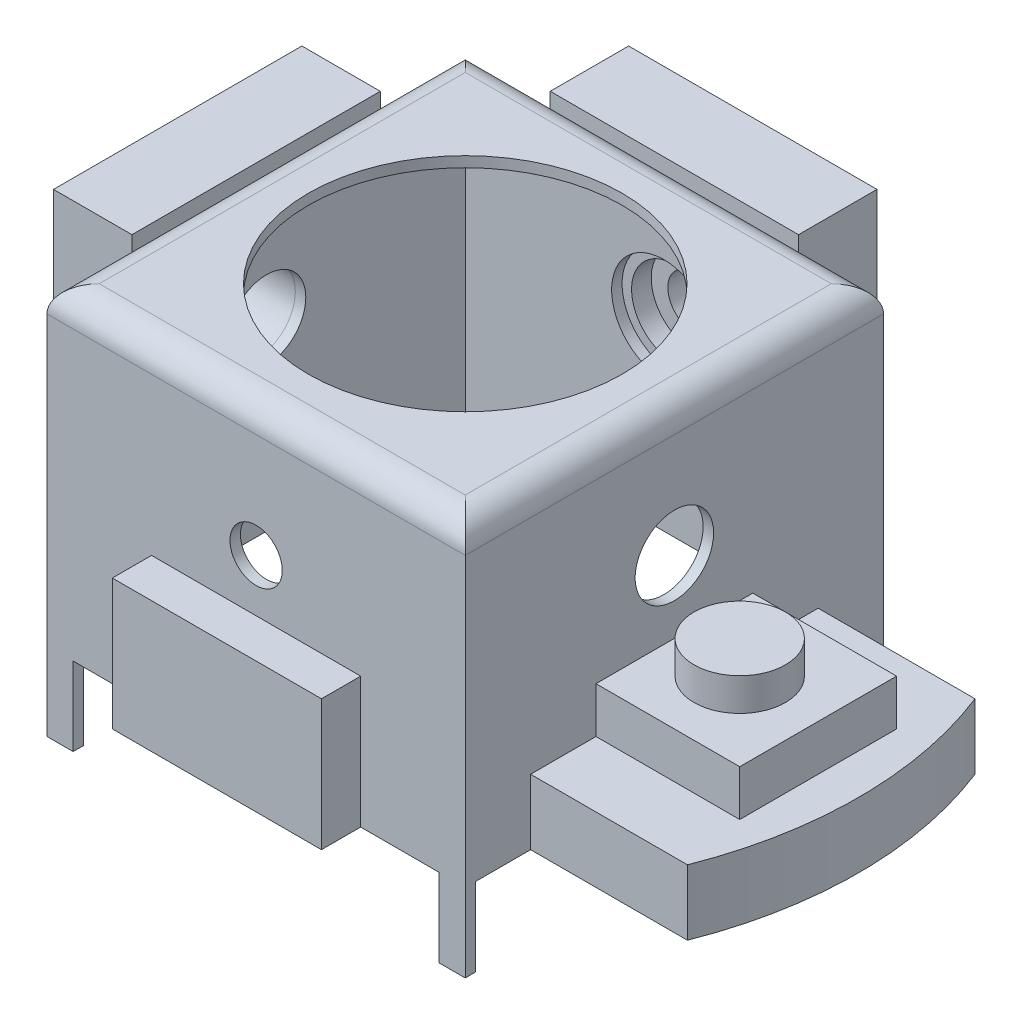
SolidWorks part; units mm, degrees
ref_plane "Front" through (0, 0, 0) normal (0, 0, 1) x (1, 0, 0)
ref_plane "Top" through (0, 0, 0) normal (0, 1, 0) x (1, 0, 0)
ref_plane "Right" through (0, 0, 0) normal (1, 0, 0) x (0, 0, -1)
sketch "Sketch1" plane through (0, 0, 0) normal (0, 1, 0) x (1, 0, 0)
  line L1 (-8, -8) -> (8, -8)
  line L2 (-8, -8) -> (-8, 8)
  line L3 (-8, 8) -> (8, 8)
  line L4 (8, -8) -> (8, 8)
  line L5 (-8, -8) -> (8, 8) construction
  line L6 (-8, 8) -> (8, -8) construction
  point P0 (0, 0)
  dimension "D1" = 16
extrude "Extrude1" add sketch "Sketch1" along normal blind 12
fillet "Fillet1" radius 1 4 edges at (0, 12, 8) (-8, 12, 0) (0, 12, -8) (8, 12, 0)
shell "Shell1" thickness 0.4
sketch "Sketch2" plane through (0, 12, 0) normal (0, 1, 0) x (1, 0, 0)
  circle A0 centre (0, 0) radius 6
  dimension "D1" = 12
extrude "Extrude2" cut sketch "Sketch2" against normal through all
sketch "Sketch4" plane through (0, 0, 0) normal (0, 1, 0) x (1, 0, 0)
  line L0 (8, -8) -> (-8, -8) construction
  line L1 (-4, -8) -> (4, -8)
  line L2 (-4, -8) -> (-4, -9.5)
  line L3 (-4, -9.5) -> (4, -9.5)
  line L4 (4, -8) -> (4, -9.5)
  line L5 (0, -6.6) -> (0, 6.6) construction
  point P6 (0, -9.5)
  dimension "D1" = 1.5
  dimension "D2" = 8
extrude "Extrude3" add sketch "Sketch4" along normal blind 5 separate body
sketch "Sketch5" plane through (0, 0, 0) normal (0, 1, 0) x (1, 0, 0)
  line L0 (-8, -8) -> (-8, 8) construction
  line L1 (-8, 4.75) -> (-11, 4.75)
  line L2 (-8, 4.75) -> (-8, -4.75)
  line L3 (-8, -4.75) -> (-11, -4.75)
  line L4 (-11, 4.75) -> (-11, -4.75)
  line L5 (-6.6, 0) -> (6.6, 0) construction
  point P6 (-11, 0)
  dimension "D1" = 9.5
  dimension "D2" = 3
extrude "Extrude4" add sketch "Sketch5" along normal blind 11 from offset 1 separate body
sketch "Sketch6" plane through (0, 0, 0) normal (0, 1, 0) x (1, 0, 0)
  line L0 (-8, 8) -> (8, 8) construction
  line L1 (-4.75, 8) -> (4.75, 8)
  line L2 (-4.75, 8) -> (-4.75, 11)
  line L3 (-4.75, 11) -> (4.75, 11)
  line L4 (4.75, 8) -> (4.75, 11)
  line L5 (0, -6.6) -> (0, 6.6) construction
  line L6 (-11, 4.75) -> (-11, -4.75) construction
  line L7 (-8, 4.75) -> (-11, 4.75) construction
  point P6 (0, 11)
extrude "Extrude5" add sketch "Sketch6" along normal blind 11 from offset 1 separate body
sketch "Sketch7" plane through (0, 0, 0) normal (0, 1, 0) x (1, 0, 0)
  line L0 (8, 5.5) -> (14, 5.5)
  line L1 (8, 8) -> (8, -8) construction
  line L2 (-1001.9415, 0) -> (48998.0585, 0) construction
  line L4 (-8.25, 0) -> (8.25, 0) construction
  line L5 (8, -5.5) -> (14, -5.5)
  line L6 (8, 5.5) -> (8, -5.5)
  arc A0 (14, 5.5) -> (14, -5.5) centre (0, 0) cw
  dimension "D1" = 6
  dimension "D2" = 11
extrude "Extrude6" add sketch "Sketch7" along normal blind 2.5 separate body
sketch "Sketch8" plane through (0, 2.5, 0) normal (0, 1, 0) x (1, 0, 0)
  line L0 (8, 5.5) -> (8, -5.5) construction
  line L1 (8, 3) -> (13.5, 3)
  line L2 (8, 3) -> (8, -3)
  line L3 (8, -3) -> (13.5, -3)
  line L4 (13.5, 3) -> (13.5, -3)
  line L5 (-8.25, 0) -> (8.25, 0) construction
  point P6 (13.5, 0)
  dimension "D1" = 6
  dimension "D2" = 5.5
extrude "Extrude7" add sketch "Sketch8" along normal blind 1.75 separate body
sketch "Sketch9" plane through (0, 4.25, 0) normal (0, 1, 0) x (1, 0, 0)
  line L0 (-8.25, 0) -> (8.25, 0) construction
  line L1 (13.5, -3) -> (13.5, 3) construction
  circle A0 centre (10.5, 0) radius 1.75
  dimension "D1" = 3.5
  dimension "D2" = 1.25
extrude "Extrude8" add sketch "Sketch9" along normal blind 1.25
sketch "Sketch10" plane through (0, 0, 0) normal (0, 0, 1) x (1, 0, 0)
  line L0 (0, -6.6) -> (0, 6.6) construction
  line L1 (11.275, 0) -> (-11.275, 0) construction
  circle A0 centre (0, 7) radius 1
  dimension "D1" = 2
  dimension "D2" = 7
extrude "Extrude9" cut sketch "Sketch10" against normal through all and the other way through all
sketch "Sketch11" plane through (0, 0, 0) normal (1, 0, 0) x (0, 0, -1)
  line L0 (0, 6.6) -> (0, -6.6) construction
  line L1 (11.275, 0) -> (-11.275, 0) construction
  circle A0 centre (0, 7) radius 1
  dimension "D1" = 2
  dimension "D2" = 7
extrude "Extrude10" cut sketch "Sketch11" against normal through all and the other way through all
sketch "Sketch12" plane through (0, 0, 0) normal (0, 1, 0) x (1, 0, 0)
  line L0 (-7.6, 7.6) -> (7.6, 7.6) construction
  line L1 (8, 8) -> (7, 8)
  line L2 (8, 8) -> (8, 7.6)
  line L3 (8, 7.6) -> (7, 7.6)
  line L4 (7, 8) -> (7, 7.6)
  line L5 (7.6, -7.6) -> (-7.6, -7.6) construction
  line L6 (-8, 8) -> (-7, 8)
  line L7 (-8, 8) -> (-8, 7.6)
  line L8 (-8, 7.6) -> (-7, 7.6)
  line L9 (-7, 8) -> (-7, 7.6)
  line L10 (8, -8) -> (7, -8)
  line L11 (8, -8) -> (8, -7.6)
  line L12 (8, -7.6) -> (7, -7.6)
  line L13 (7, -8) -> (7, -7.6)
  line L15 (-8, -8) -> (-7, -8)
  line L16 (-8, -8) -> (-8, -7.6)
  line L17 (-8, -7.6) -> (-7, -7.6)
  line L18 (-7, -8) -> (-7, -7.6)
  dimension "D1" = 1
extrude "Extrude11" add sketch "Sketch12" against normal blind 3
sketch "Sketch13" plane through (0, 0, -7.6) normal (0, 0, 1) x (1, 0, 0)
  circle A0 centre (0, 7) radius 1.5
  dimension "D1" = 3
extrude "Extrude12" cut sketch "Sketch13" against normal up to next (0.4 mm away)
sketch "Sketch14" plane through (-7.6, 0, 0) normal (1, 0, 0) x (0, 0, -1)
  circle A0 centre (0, 7) radius 1.5
  dimension "D1" = 3
extrude "Extrude13" cut sketch "Sketch14" against normal up to next (0.4 mm away)
sketch "Sketch15" plane through (-8, 0, 0) normal (1, 0, 0) x (0, 0, -1)
  circle A0 centre (0, 7) radius 1.5
  dimension "D1" = 3
extrude "Cut-Extrude1" cut sketch "Sketch15" against normal blind 1.75
sketch "Sketch17" plane through (0, 0, -8) normal (0, 0, 1) x (1, 0, 0)
  circle A0 centre (0, 7) radius 1.6375
  dimension "D1" = 3.275
extrude "Cut-Extrude2" cut sketch "Sketch17" against normal blind 0.75
sketch "Sketch18" plane through (8, 0, 0) normal (1, 0, 0) x (0, 0, -1)
  circle A0 centre (0, 7) radius 1.5
  dimension "D1" = 3
extrude "Cut-Extrude3" cut sketch "Sketch18" against normal up to next (0.4 mm away)
sketch "Sketch19" plane through (0, 0, -7.6) normal (0, 0, 1) x (1, 0, 0)
  circle A0 centre (0, 7) radius 2
  dimension "D1" = 4
extrude "Extrude14" cut sketch "Sketch19" against normal up to next (0.4 mm away)
